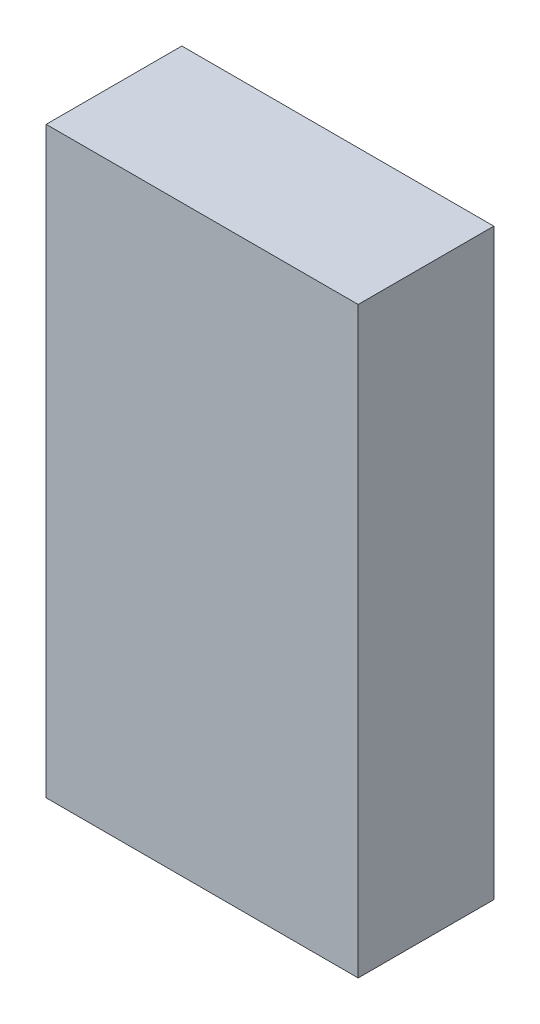
SolidWorks part; units mm, degrees
ref_plane "Front Plane" through (0, 0, 0) normal (0, 0, 1) x (1, 0, 0)
ref_plane "Top Plane" through (0, 0, 0) normal (0, 1, 0) x (1, 0, 0)
ref_plane "Right Plane" through (0, 0, 0) normal (1, 0, 0) x (0, 0, -1)
sketch "Sketch1" plane through (0, 0, 0) normal (0, 0, 1) x (1, 0, 0)
  line L1 (0, 0) -> (115, 0)
  line L2 (0, 0) -> (0, 215)
  line L3 (0, 215) -> (115, 215)
  line L4 (115, 0) -> (115, 215)
  dimension "D1" = 115
  dimension "D2" = 215
extrude "Boss-Extrude1" add sketch "Sketch1" along normal blind 50
